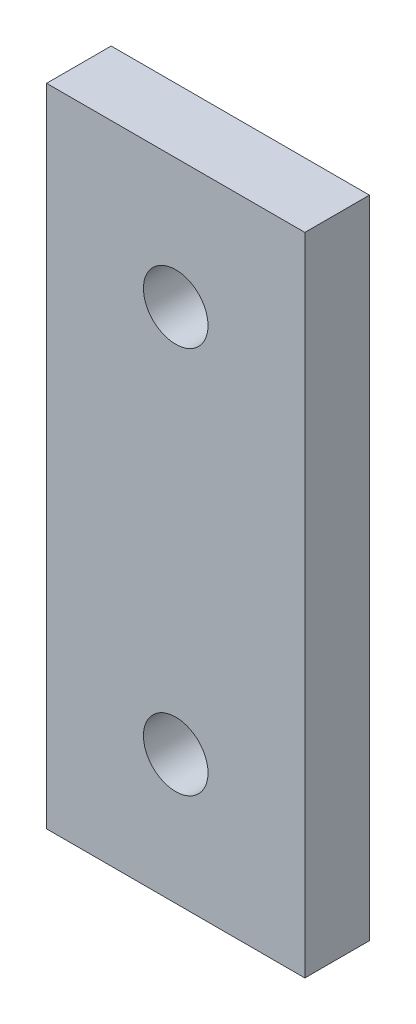
SolidWorks part; units mm, degrees
ref_plane "前视基准面" through (0, 0, 0) normal (0, 0, 1) x (1, 0, 0)
ref_plane "上视基准面" through (0, 0, 0) normal (0, 1, 0) x (1, 0, 0)
ref_plane "右视基准面" through (0, 0, 0) normal (1, 0, 0) x (0, 0, -1)
sketch "草图1" plane through (0, 0, 0) normal (0, 0, 1) x (1, 0, 0)
  line L1 (-10, -25) -> (10, -25)
  line L2 (-10, -25) -> (-10, 25)
  line L3 (-10, 25) -> (10, 25)
  line L4 (10, -25) -> (10, 25)
  line L5 (0, 25) -> (0, -25) construction
  line L6 (-10, 0) -> (10, 0) construction
  point P0 (0, 0)
  dimension "D1" = 20
  dimension "D2" = 50
extrude "凸台-拉伸1" add sketch "草图1" along normal blind 5
sketch "草图2" plane through (0, 0, 5) normal (0, 0, 1) x (1, 0, 0)
  line L0 (10, 25) -> (-10, 25) construction
  line L2 (10, -25) -> (10, 25) construction
  line L3 (-10, -25) -> (10, -25) construction
  circle A0 centre (0, 15) radius 2.5
  circle A1 centre (0, -15) radius 2.5
  point P12 (10, -11.3717)
  point P13 (3.8827, -8.9994)
  dimension "D3" = 5
  dimension "D6" = 5
  dimension "D1" = 10
  dimension "D2" = 10
  dimension "D4" = 10
  dimension "D5" = 10
extrude "切除-拉伸1" cut sketch "草图2" against normal through all
